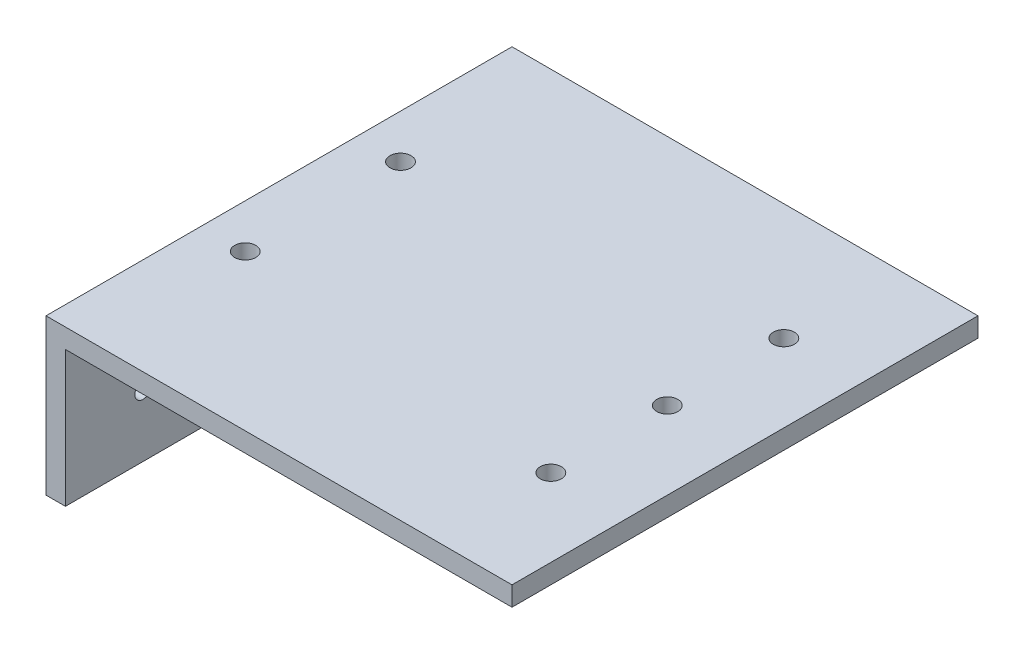
SolidWorks part; units mm, degrees
ref_plane "Front Plane" through (0, 0, 0) normal (0, 0, 1) x (1, 0, 0)
ref_plane "Top Plane" through (0, 0, 0) normal (0, 1, 0) x (1, 0, 0)
ref_plane "Right Plane" through (0, 0, 0) normal (1, 0, 0) x (0, 0, -1)
sketch "Sketch2" plane through (0, 0, 0) normal (0, 0, 1) x (1, 0, 0)
  line L0 (0, 0) -> (-76.2, 0)
  line L1 (-76.2, 0) -> (-76.2, -25.4)
  line L2 (-76.2, -25.4) -> (-73.025, -25.4)
  line L3 (-73.025, -25.4) -> (-73.025, -3.175)
  line L4 (-73.025, -3.175) -> (0, -3.175)
  line L5 (0, -3.175) -> (0, 0)
  dimension "D1" = 76.2
  dimension "D2" = 25.4
  dimension "D3" = 3.175
  dimension "D4" = 3.175
extrude "Boss-Extrude1" add sketch "Sketch2" along normal blind 76.2
sketch "Sketch7" plane through (-76.2, 0, 0) normal (-1, 0, 0) x (0, 0, 1)
  line L1 (0, 0) -> (0, -25.4) construction
  line L2 (0, -15.24) -> (38.1, -15.24) construction
  line L7 (36.449, -16.9885) -> (39.751, -13.4915) construction
  line L8 (36.449, -13.4915) -> (39.751, -16.9885) construction
  circle A0 centre (38.1, -15.24) radius 3.175
  dimension "D1" = 38.1
  dimension "D2" = 3.302
extrude "Cut-Extrude1" cut sketch "Sketch7" against normal up to next
hole_wizard "Tap Drill for #8-32 Tap2" positions "Sketch10" profile "Sketch9" hole size "#8-32" standard "ANSI Inch" end condition through all
sketch "Sketch10" plane through (0, 0, 0) normal (0, 1, 0) x (1, 0, 0)
  line L0 (0, 0) -> (-76.2, 0) construction
  line L1 (0, -76.2) -> (0, 0) construction
  point P0 (-12.7, -19.05)
  point P2 (-12.7, -38.1)
  point P4 (-12.7, -57.15)
  dimension "D1" = 19.05
  dimension "D2" = 19.05
  dimension "D3" = 19.05
  dimension "D4" = 12.7
sketch "Sketch9" plane through (-12.7, 0, 19.05) normal (1, 0, 0) x (0, 0, 1)
  line L0 (0, 0) -> (0, 25.4)
  line L1 (0, 25.4) -> (1.7272, 25.4)
  line L2 (1.7272, 25.4) -> (1.7272, 0)
  line L5 (1.7272, 0) -> (0, 0)
  line L11 (0, -6.35) -> (0, 107.95) construction
  dimension "Thru Hole Dia." = 3.4544
  dimension "Thru Hole Depth" = 25.4
hole_wizard "Tap Drill for #8-32 Tap4" positions "Sketch15" profile "Sketch14" hole size "#8-32" standard "ANSI Inch" end condition up to next
sketch "Sketch15" plane through (0, 0, 0) normal (0, 1, 0) x (1, 0, 0)
  line L0 (0, 0) -> (-76.2, 0) construction
  point P0 (-69.0285, -25.4)
  point P2 (-69.0285, -50.8)
  dimension "D1" = 25.4
  dimension "D2" = 25.4
sketch "Sketch14" plane through (-69.0285, 0, 25.4) normal (1, 0, 0) x (0, 0, 1)
  line L0 (0, 0) -> (0, 3.175)
  line L1 (0, 3.175) -> (1.7272, 3.175)
  line L2 (1.7272, 3.175) -> (1.7272, 0)
  line L5 (1.7272, 0) -> (0, 0)
  line L11 (0, -6.35) -> (0, 107.95) construction
  dimension "Thru Hole Dia." = 3.4544
  dimension "Thru Hole Depth" = 3.175
hole_wizard "Tap Drill for #6-32 Tap1" positions "Sketch17" profile "Sketch16" hole size "#6-32" standard "ANSI Inch" end condition up to next
sketch "Sketch17" plane through (-76.2, 0, 0) normal (-1, 0, 0) x (0, 0, 1)
  line L0 (76.2, 0) -> (0, 0) construction
  line L1 (76.2, 0) -> (76.2, -25.4) construction
  point P0 (50.8, -15.24)
  point P2 (63.5, -15.24)
  dimension "D1" = 12.7
  dimension "D2" = 15.24
  dimension "D3" = 12.7
sketch "Sketch16" plane through (-76.2, -15.24, 50.8) normal (0, 1, 0) x (0, 0, 1)
  line L0 (0, 0) -> (0, 3.175)
  line L1 (0, 3.175) -> (1.3525, 3.175)
  line L2 (1.3525, 3.175) -> (1.3525, 0)
  line L5 (1.3525, 0) -> (0, 0)
  line L11 (0, -6.35) -> (0, 107.95) construction
  dimension "Thru Hole Dia." = 2.7051
  dimension "Thru Hole Depth" = 3.175
